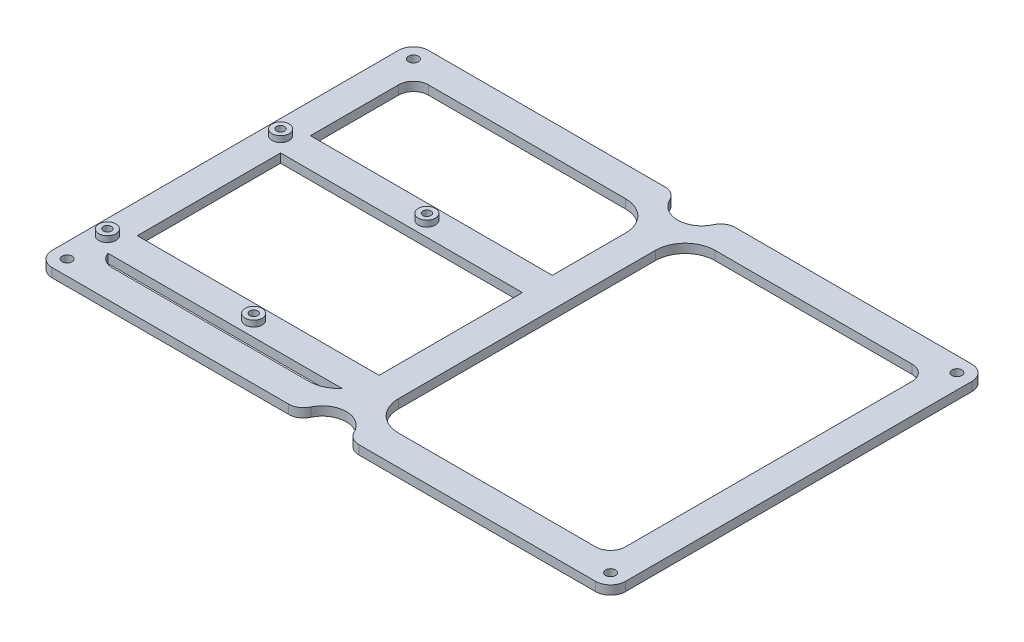
SolidWorks part; units mm, degrees
ref_plane "Front Plane" through (0, 0, 0) normal (0, 0, 1) x (1, 0, 0)
ref_plane "Top Plane" through (0, 0, 0) normal (0, 1, 0) x (1, 0, 0)
ref_plane "Right Plane" through (0, 0, 0) normal (1, 0, 0) x (0, 0, -1)
sketch "Sketch1" plane through (0, 0, 0) normal (0, 1, 0) x (1, 0, 0)
  line L0 (-91, 63) -> (-11.7792, 63)
  line L13 (-91, -58) -> (91, -58) construction
  line L14 (-91, -58) -> (-91, 58) construction
  line L15 (-91, 58) -> (91, 58) construction
  line L16 (91, -58) -> (91, 58) construction
  line L17 (-91, -58) -> (91, 58) construction
  line L18 (-91, 58) -> (91, -58) construction
  line L19 (96, -58) -> (96, 58)
  line L20 (-91, -63) -> (-11.7792, -63)
  line L21 (-96, -58) -> (-96, 58)
  line L22 (-81, 53) -> (-15, 53)
  line L23 (86, -48) -> (86, 48)
  line L24 (-81, -53) -> (-15, -53)
  line L25 (-86, -48) -> (-86, 48)
  line L26 (0, 56.5) -> (0, -56.5) construction
  line L27 (-5, 43) -> (-5, -43)
  line L28 (5, 43) -> (5, -43)
  line L29 (-5, 56.5) -> (-5, -56.5) construction
  line L30 (15, -53) -> (81, -53)
  line L31 (-86, -53) -> (86, -53) construction
  line L32 (5, 56.5) -> (5, -56.5) construction
  line L33 (11.7792, -63) -> (91, -63)
  line L34 (-96, -63) -> (96, -63) construction
  line L35 (15, 53) -> (81, 53)
  line L36 (-86, 53) -> (86, 53) construction
  line L37 (11.7792, 63) -> (91, 63)
  line L38 (-96, 63) -> (96, 63) construction
  line L39 (86, -53) -> (86, 53) construction
  line L40 (-86, -53) -> (-86, 53) construction
  line L41 (-96, -63) -> (-96, 63) construction
  line L42 (96, -63) -> (96, 63) construction
  circle A0 centre (-91, 58) radius 1.65
  circle A1 centre (91, 58) radius 1.65
  circle A2 centre (91, -58) radius 1.65
  circle A3 centre (-91, -58) radius 1.65
  circle A4 centre (0, -63.5) radius 7 construction
  circle A5 centre (0, 63.5) radius 7 construction
  arc A6 (-7.2488, 60.1154) -> (7.2488, 60.1154) centre (0, 63.5) ccw
  arc A7 (7.2488, -60.1154) -> (-7.2488, -60.1154) centre (0, -63.5) ccw
  circle A8 centre (0, -63.5) radius 8 construction
  circle A9 centre (0, 63.5) radius 8 construction
  arc A10 (15, -53) -> (5, -43) centre (15, -43) cw
  arc A11 (-5, -43) -> (-15, -53) centre (-15, -43) cw
  arc A12 (15, 53) -> (5, 43) centre (15, 43) ccw
  arc A13 (-15, 53) -> (-5, 43) centre (-15, 43) cw
  arc A14 (7.2488, 60.1154) -> (11.7792, 63) centre (11.7792, 58) cw
  arc A15 (-7.2488, 60.1154) -> (-11.7792, 63) centre (-11.7792, 58) ccw
  arc A16 (7.2488, -60.1154) -> (11.7792, -63) centre (11.7792, -58) ccw
  arc A17 (-7.2488, -60.1154) -> (-11.7792, -63) centre (-11.7792, -58) cw
  arc A18 (86, -48) -> (81, -53) centre (81, -48) cw
  arc A19 (-81, -53) -> (-86, -48) centre (-81, -48) cw
  arc A20 (81, 53) -> (86, 48) centre (81, 48) cw
  arc A21 (-81, 53) -> (-86, 48) centre (-81, 48) ccw
  arc A22 (-91, 63) -> (-96, 58) centre (-91, 58) ccw
  arc A23 (91, 63) -> (96, 58) centre (91, 58) cw
  arc A24 (96, -58) -> (91, -63) centre (91, -58) cw
  arc A25 (-91, -63) -> (-96, -58) centre (-91, -58) cw
  point P0 (0, 0)
  point P4 (0, -63)
  point P16 (0, -56.5)
  point P27 (0, 0)
  point P29 (0, 56.5)
  point P57 (7.9844, 63)
  point P62 (7.9844, -63)
  dimension "D1" = 182
  dimension "D3" = 3.3
  dimension "D7" = 14
  dimension "D8" = 1
  dimension "D11" = 10
  dimension "D12" = 5
  dimension "D13" = 5
  dimension "D14" = 5
  dimension "D2" = 116
  dimension "D6" = 113
  dimension "D4" = 5
  dimension "D5" = 5
  dimension "D9" = 5
  dimension "D10" = 5
extrude "Boss-Extrude1" add sketch "Sketch1" along normal blind 3
sketch "Sketch2" plane through (0, 3, 0) normal (0, 1, 0) x (1, 0, 0)
  line L0 (-86, 8.5) -> (-42, 8.5)
  line L1 (-94.5, 37) -> (-38.5, 37) construction
  line L2 (-94.5, 37) -> (-94.5, -48) construction
  line L3 (-94.5, -48) -> (-38.5, -48) construction
  line L4 (-38.5, 37) -> (-38.5, -48) construction
  line L5 (-91, 13.5) -> (-42, 13.5) construction
  line L6 (-91, 13.5) -> (-91, -44.5) construction
  line L7 (-91, -44.5) -> (-42, -44.5) construction
  line L8 (-42, 13.5) -> (-42, -44.5) construction
  line L9 (-85.7697, -49.5) -> (-42, -49.5)
  line L10 (-86, 18.5) -> (-42, 18.5)
  line L11 (-86, -39.5) -> (-42, -39.5)
  line L12 (-5, -43) -> (-5, 43) construction
  line L14 (-86, 48) -> (-86, -48) construction
  line L15 (-5, -43) -> (-5, -39.5)
  line L17 (-86, 48) -> (-86, 8.5)
  line L18 (-91, 8.5) -> (-42, 8.5) construction
  line L19 (-91, 18.5) -> (-42, 18.5) construction
  line L20 (-91, -39.5) -> (-42, -39.5) construction
  line L21 (-91, -49.5) -> (-42, -49.5) construction
  line L22 (-86, -39.5) -> (-86, -48)
  line L23 (-42, 8.5) -> (-5, 8.5)
  line L24 (-42, 18.5) -> (-5, 18.5)
  line L25 (-42, -39.5) -> (-5, -39.5)
  line L26 (-42, -49.5) -> (-7.4007, -49.5)
  line L27 (-5, 8.5) -> (-5, 18.5)
  circle A0 centre (-91, -44.5) radius 1.35 construction
  circle A1 centre (-42, -44.5) radius 1.35 construction
  circle A2 centre (-42, 13.5) radius 1.35 construction
  circle A3 centre (-91, 13.5) radius 1.35 construction
  arc A4 (-15, -53) -> (-5, -43) centre (-15, -43) ccw construction
  arc A5 (-86, -48) -> (-81, -53) centre (-81, -48) ccw construction
  arc A6 (-7.4007, -49.5) -> (-5, -43) centre (-15, -43) ccw
  arc A7 (-86, -48) -> (-85.7697, -49.5) centre (-81, -48) ccw
  point P12 (-91, -58)
  point P37 (0, 0)
  arc M35 (-5, -43) -> (-15, -53) centre (-15, -43) cw
  arc M37 (-81, -53) -> (-86, -48) centre (-81, -48) cw
  line M38 (-86, -48) -> (-86, 48)
  line M42 (-5, 43) -> (-5, -43)
  dimension "D3" = 49
  dimension "D7" = 2.7
  dimension "D1" = 85
  dimension "D2" = 56
  dimension "D4" = 58
  dimension "D5" = 3.5
  dimension "D6" = 3.5
  dimension "D8" = 10
  dimension "D9" = 5
  dimension "D10" = 5
extrude "Boss-Extrude2" add sketch "Sketch2" against normal up to surface (3 mm away) contours L9 L26 L25 L11 M35 M42 M38 M37 | L24 L10 L0 L23 M38 M42 up to face at (91, 0, 59.65)
sketch "Sketch3" plane through (0, 3, 0) normal (0, 1, 0) x (1, 0, 0)
  circle A0 centre (-42, -44.5) radius 1.35 construction
  circle A1 centre (-91, -44.5) radius 1.35 construction
  circle A2 centre (-42, 13.5) radius 1.35 construction
  circle A3 centre (-91, 13.5) radius 1.35 construction
  circle A4 centre (-42, -44.5) radius 1.35
  circle A5 centre (-91, -44.5) radius 1.35
  circle A6 centre (-42, 13.5) radius 1.35
  circle A7 centre (-91, 13.5) radius 1.35
extrude "Cut-Extrude1" cut sketch "Sketch3" against normal up to surface (3 mm away) up to face at (-45.5, 0, 15.5)
sketch "Sketch4" plane through (0, 3, 0) normal (0, 1, 0) x (1, 0, 0)
  circle A0 centre (-91, -44.5) radius 1.35 construction
  circle A1 centre (-42, -44.5) radius 1.35 construction
  circle A2 centre (-42, 13.5) radius 1.35 construction
  circle A3 centre (-91, 13.5) radius 1.35 construction
  circle A4 centre (-91, -44.5) radius 1.35
  circle A5 centre (-42, -44.5) radius 1.35
  circle A6 centre (-42, 13.5) radius 1.35
  circle A7 centre (-91, 13.5) radius 1.35
  circle A8 centre (-91, 13.5) radius 2.85
  circle A9 centre (-91, -44.5) radius 2.85
  circle A30 centre (-42, -44.5) radius 2.85
  circle A31 centre (-42, 13.5) radius 2.85
extrude "Boss-Extrude3" add sketch "Sketch4" along normal blind 2
